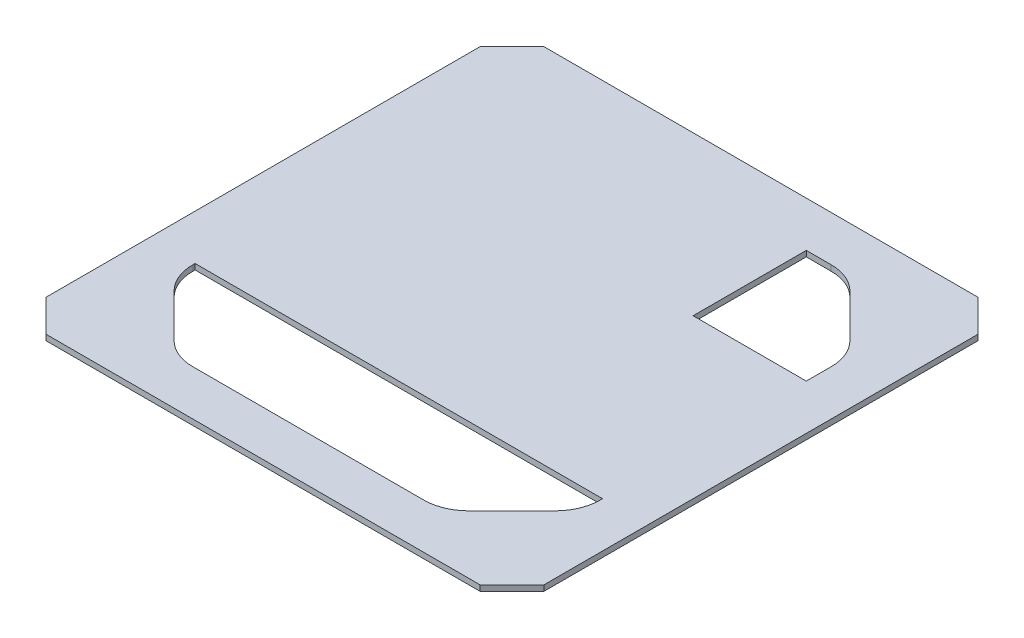
SolidWorks part; units mm, degrees
ref_plane "Front Plane" through (0, 0, 0) normal (0, 0, 1) x (1, 0, 0)
ref_plane "Top Plane" through (0, 0, 0) normal (0, 1, 0) x (1, 0, 0)
ref_plane "Right Plane" through (0, 0, 0) normal (1, 0, 0) x (0, 0, -1)
sketch "Sketch1" plane through (0, 0, 0) normal (0, 1, 0) x (1, 0, 0)
  line L0 (-139.7, 73.5201) -> (-121.7395, 91.4807)
  line L1 (-121.7395, 91.4807) -> (121.7395, 91.4807)
  line L2 (-139.7, 73.5201) -> (-139.7, -169.9588)
  line L3 (139.7, 73.5201) -> (139.7, -169.9588)
  line L4 (139.7, 73.5201) -> (121.7395, 91.4807)
  line L5 (0, 91.4807) -> (0, -187.9193) construction
  line L6 (-139.7, -48.2193) -> (139.7, -48.2193) construction
  line L7 (139.7, -169.9588) -> (121.7395, -187.9193)
  line L8 (-121.7395, -187.9193) -> (121.7395, -187.9193)
  line L9 (-139.7, -169.9588) -> (-121.7395, -187.9193)
  line L10 (-247.4631, 199.2437) -> (247.4631, 199.2437) construction
  line L11 (247.4631, 199.2437) -> (247.4631, -295.6824) construction
  line L12 (247.4631, -295.6824) -> (-247.4631, -295.6824) construction
  line L13 (-247.4631, -295.6824) -> (-247.4631, 199.2437) construction
  line L14 (-247.4631, 199.2437) -> (247.4631, -295.6824) construction
  line L15 (-247.4631, -295.6824) -> (247.4631, 199.2437) construction
  line L16 (-247.4631, 199.2437) -> (-130.7197, 82.5004) construction
  point P11 (0, -48.2193)
  point P20 (0, -48.2193)
  point P21 (-130.7197, 82.5004)
  dimension "D1" = 279.4
  dimension "D2" = 279.4
  dimension "D3" = 25.4
  dimension "D4" = 165.1
extrude "Boss-Extrude1" add sketch "Sketch1" along normal blind 3.175
sketch "Sketch2" plane through (0, 3.175, 0) normal (0, 1, 0) x (1, 0, 0)
  line L0 (-139.7, -48.2193) -> (139.7, -48.2193) construction
  line L1 (-139.7, 73.5201) -> (-139.7, -169.9588) construction
  line L2 (-103.779, 37.5991) -> (-114.3, 27.0781)
  line L3 (0, 91.4807) -> (0, -187.9193) construction
  line L4 (-85.8185, 55.5596) -> (-75.2974, 66.0807)
  line L5 (-130.7197, 82.5004) -> (-94.7987, 46.5794) construction
  line L6 (121.7395, 91.4807) -> (-121.7395, 91.4807) construction
  line L7 (-121.7395, -187.9193) -> (121.7395, -187.9193) construction
  line L8 (139.7, -169.9588) -> (139.7, 73.5201) construction
  line L9 (-114.3, 27.0781) -> (-114.3, -123.5168)
  line L10 (-121.7395, 91.4807) -> (-139.7, 73.5201) construction
  line L11 (-75.2974, 66.0807) -> (75.2974, 66.0807)
  line L12 (114.3, 27.0781) -> (114.3, -123.5168)
  line L13 (85.8185, 55.5596) -> (103.779, 37.5991)
  line L14 (85.8185, 55.5596) -> (75.2974, 66.0807)
  line L15 (103.779, 37.5991) -> (114.3, 27.0781)
  line L16 (-85.8185, -151.9983) -> (-103.779, -134.0378)
  line L17 (103.779, -134.0378) -> (114.3, -123.5168)
  line L18 (85.8185, -151.9983) -> (75.2974, -162.5193)
  line L19 (85.8185, -151.9983) -> (103.779, -134.0378)
  line L20 (-75.2974, -162.5193) -> (75.2974, -162.5193)
  line L21 (-85.8185, -151.9983) -> (-75.2974, -162.5193)
  line L22 (-103.779, -134.0378) -> (-114.3, -123.5168)
  line L23 (-85.8185, 55.5596) -> (-103.779, 37.5991)
  point P22 (114.3, -48.2193)
  point P26 (-114.3, -48.2193)
  dimension "D3" = 25.4
  dimension "D4" = 25.4
  dimension "D1" = 50.8
  dimension "D2" = 25.4
extrude "Cut-Extrude4" cut sketch "Sketch2" against normal through all
sketch "Sketch5" plane through (0, 3.175, 0) normal (0, 1, 0) x (1, 0, 0)
  line L0 (0, 91.4807) -> (0, -187.9193) construction
  line L1 (121.7395, 91.4807) -> (-121.7395, 91.4807) construction
  line L2 (139.7, -48.2193) -> (-139.7, -48.2193) construction
  line L3 (139.7, -169.9588) -> (139.7, 73.5201) construction
  line L4 (-121.7395, -187.9193) -> (121.7395, -187.9193) construction
  line L5 (-139.7, 73.5201) -> (-139.7, -169.9588) construction
  line L6 (-247.4631, 199.2437) -> (247.4631, 199.2437) construction
  line L7 (247.4631, 199.2437) -> (247.4631, -295.6824) construction
  line L8 (247.4631, -295.6824) -> (-247.4631, -295.6824) construction
  line L9 (-247.4631, -295.6824) -> (-247.4631, 199.2437) construction
  line L10 (139.7, -48.2193) -> (358.8347, -48.2193) construction
  line L11 (0, 91.4807) -> (0, 307.0068) construction
  line L12 (-247.4631, 199.2437) -> (247.4631, -295.6824) construction
  line L13 (247.4631, 199.2437) -> (-247.4631, -295.6824) construction
  line L14 (-121.7395, 91.4807) -> (-139.7, 73.5201) construction
  line L15 (-247.4631, 199.2437) -> (-94.7987, 46.5794) construction
  line L16 (-75.2974, 66.0807) -> (-114.3, 27.0781) construction
  circle A0 centre (-121.7395, 73.5201) radius 2.54
  circle A1 centre (-103.779, 55.5596) radius 2.54
  circle A2 centre (103.779, 55.5596) radius 2.54
  circle A3 centre (121.7395, 73.5201) radius 2.54
  circle A4 centre (121.7395, -169.9588) radius 2.54
  circle A5 centre (103.779, -151.9983) radius 2.54
  circle A6 centre (-103.779, -151.9983) radius 2.54
  circle A7 centre (-121.7395, -169.9588) radius 2.54
  point P9 (247.4631, -48.2193)
  point P19 (0, 199.2437)
  dimension "D2" = 5.08
  dimension "D3" = 5.08
  dimension "D1" = 165.1
  dimension "D4" = 25.4
  dimension "D5" = 12.7
extrude "Cut-Extrude3" [suppressed] cut sketch "Sketch5" against normal through all
sketch "Sketch4" plane through (0, 3.175, 0) normal (0, 1, 0) x (1, 0, 0)
  line L0 (-139.7, -48.2193) -> (171.6111, -48.2193) construction
  line L1 (-139.7, 73.5201) -> (-139.7, -169.9588) construction
  line L2 (121.7395, 91.4807) -> (-121.7395, 91.4807) construction
  line L3 (0, -48.2193) -> (0, -217.7016) construction
  line L4 (139.7, -169.9588) -> (139.7, 73.5201) construction
  line L5 (0, -48.2193) -> (0, 293.0757) construction
  circle A0 centre (0, 81.3207) radius 2.159
  circle A1 centre (-44.45, 81.3207) radius 2.159
  circle A2 centre (44.45, 81.3207) radius 2.159
  circle A3 centre (-22.225, 81.3207) radius 2.159
  circle A4 centre (22.225, 81.3207) radius 2.159
  circle A5 centre (-129.54, -48.2193) radius 2.159
  circle A6 centre (-129.54, -25.9943) radius 2.159
  circle A7 centre (-129.54, -3.7693) radius 2.159
  circle A8 centre (129.54, -48.2193) radius 2.159
  circle A9 centre (129.54, -25.9943) radius 2.159
  circle A10 centre (129.54, -3.7693) radius 2.159
  circle A11 centre (129.54, -92.6693) radius 2.159
  circle A12 centre (129.54, -70.4443) radius 2.159
  circle A13 centre (-129.54, -92.6693) radius 2.159
  circle A14 centre (-129.54, -70.4443) radius 2.159
  circle A15 centre (22.225, -177.7593) radius 2.159
  circle A16 centre (-22.225, -177.7593) radius 2.159
  circle A17 centre (44.45, -177.7593) radius 2.159
  circle A18 centre (-44.45, -177.7593) radius 2.159
  circle A19 centre (0, -177.7593) radius 2.159
  circle A20 centre (-66.675, 81.3207) radius 2.159
  circle A21 centre (66.675, 81.3207) radius 2.159
  circle A22 centre (-129.54, 18.4557) radius 2.159
  circle A23 centre (129.54, 18.4557) radius 2.159
  circle A24 centre (129.54, -114.8943) radius 2.159
  circle A25 centre (66.675, -177.7593) radius 2.159
  circle A26 centre (-66.675, -177.7593) radius 2.159
  circle A27 centre (-129.54, -114.8943) radius 2.159
  circle A28 centre (-129.54, -137.1193) radius 2.159
  circle A29 centre (-129.54, 40.6807) radius 2.159
  circle A30 centre (129.54, 40.6807) radius 2.159
  circle A31 centre (129.54, -137.1193) radius 2.159
  point P48 (0, 91.4807)
  dimension "D1" = 4.318
  dimension "D2" = 4.318
  dimension "D3" = 4.318
  dimension "D4" = 4.318
  dimension "D5" = 4.318
  dimension "D6" = 4.318
  dimension "D7" = 4.318
  dimension "D8" = 4.318
  dimension "D9" = 4.318
  dimension "D10" = 4.318
  dimension "D11" = 4.318
  dimension "D23" = 4.318
  dimension "D24" = 4.318
  dimension "D27" = 4.318
  dimension "D28" = 4.318
  dimension "D31" = 4.318
  dimension "D12" = 22.225
  dimension "D13" = 22.225
  dimension "D14" = 22.225
  dimension "D15" = 22.225
  dimension "D16" = 22.225
  dimension "D17" = 22.225
  dimension "D18" = 22.225
  dimension "D19" = 22.225
  dimension "D20" = 10.16
  dimension "D21" = 10.16
  dimension "D22" = 10.16
  dimension "D25" = 22.225
  dimension "D26" = 22.225
  dimension "D29" = 22.225
  dimension "D30" = 22.225
  dimension "D32" = 22.225
extrude "Cut-Extrude2" [suppressed] cut sketch "Sketch4" against normal through all
fillet "Fillet1" radius 25.4 8 edges at (114.3, 1.5875, 123.5168) (75.2974, 1.5875, 162.5193) (-75.2974, 1.5875, 162.5193) (-114.3, 1.5875, 123.5168) (114.3, 1.5875, -27.0781) (75.2974, 1.5875, -66.0807) (-114.3, 1.5875, -27.0781) (-75.2974, 1.5875, -66.0807)
sketch "Sketch6" plane through (0, 3.175, 0) normal (0, 1, 0) x (1, 0, 0)
  line L0 (-139.7, 73.5201) -> (-139.7, -169.9588) construction
  line L1 (50.8, 2.5807) -> (139.7, 2.5807)
  line L2 (-139.7, 2.5807) -> (-139.7, -111.7193)
  line L3 (-139.7, -111.7193) -> (139.7, -111.7193)
  line L4 (139.7, 2.5807) -> (139.7, -111.7193)
  line L5 (139.7, -169.9588) -> (139.7, 73.5201) construction
  line L6 (121.7395, 91.4807) -> (-121.7395, 91.4807) construction
  line L7 (-121.7395, -187.9193) -> (121.7395, -187.9193) construction
  line L10 (50.8, 2.5807) -> (50.8, 73.5201)
  line L11 (50.8, 73.5201) -> (-139.7, 73.5201)
  line L12 (-139.7, 2.5807) -> (-139.7, 73.5201)
  point P16 (-139.7, 73.5201)
  dimension "D1" = 88.9
  dimension "D2" = 76.2
  dimension "D3" = 88.9
extrude "Boss-Extrude2" add sketch "Sketch6" against normal up to surface (3.175 mm away) up to face at (0, 0, 48.2193)
